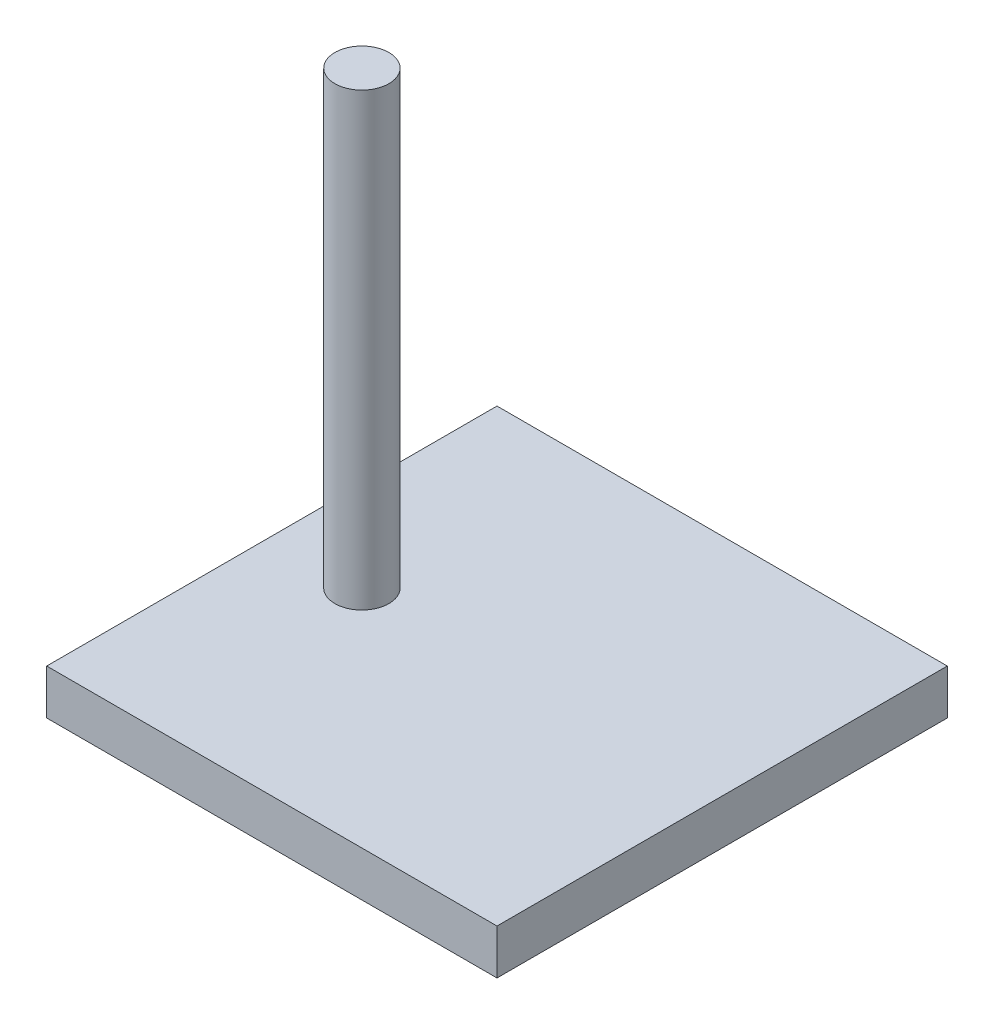
SolidWorks part; units mm, degrees
ref_plane "Front Plane" through (0, 0, 0) normal (0, 0, 1) x (1, 0, 0)
ref_plane "Top Plane" through (0, 0, 0) normal (0, 1, 0) x (1, 0, 0)
ref_plane "Right Plane" through (0, 0, 0) normal (1, 0, 0) x (0, 0, -1)
sketch "Sketch1" plane through (0, 0, 0) normal (0, 1, 0) x (1, 0, 0)
  line L0 (-50, 50) -> (50, 50)
  line L1 (-50, 50) -> (-50, -50)
  line L2 (50, 50) -> (50, -50)
  line L3 (-50, -50) -> (50, -50)
  line L4 (-50, 50) -> (50, -50) construction
  line L5 (50, 50) -> (-50, -50) construction
  point P1 (0, 0)
  dimension "D1" = 100
  dimension "D2" = 100
extrude "Boss-Extrude1" add sketch "Sketch1" along normal blind 10
sketch "Sketch2" plane through (0, 10, 0) normal (0, 1, 0) x (1, 0, 0)
  line L0 (-50, 50) -> (-50, -50) construction
  circle A0 centre (-30, 0) radius 6
  point P0 (-30, 0)
  point P1 (-50, 0)
  dimension "D1" = 20
extrude "Boss-Extrude2" add sketch "Sketch2" along normal blind 100
